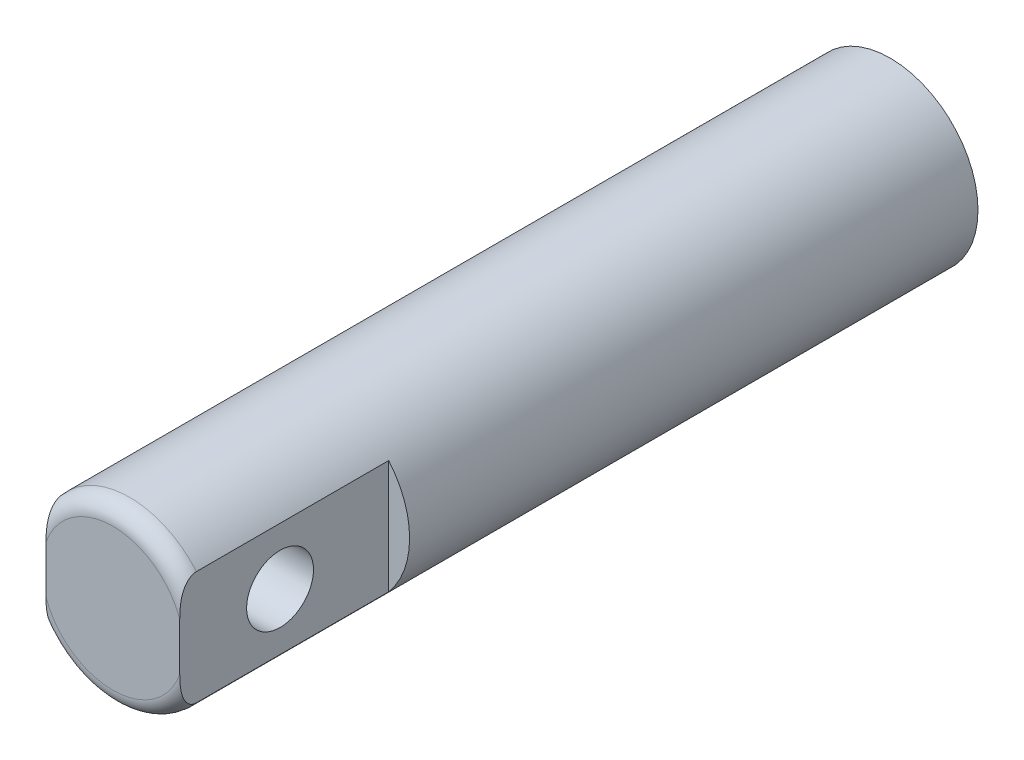
SolidWorks part; units mm, degrees
ref_plane "Спереди" through (0, 0, 0) normal (0, 0, 1) x (1, 0, 0)
ref_plane "Сверху" through (0, 0, 0) normal (0, 1, 0) x (1, 0, 0)
ref_plane "Справа" through (0, 0, 0) normal (1, 0, 0) x (0, 0, -1)
sketch "Эскиз1" plane through (0, 0, 0) normal (0, 0, 1) x (1, 0, 0)
  circle A1 centre (0, 0) radius 10.5
  dimension "D2" = 21
extrude "Вытянуть1" add sketch "Эскиз1" along normal blind 93
sketch "Эскиз2" plane through (0, 0, 0) normal (0, 0, -1) x (-1, 0, 0)
  circle A0 centre (0, 0) radius 5.25
  dimension "D1" = 10.5
extrude "Вытянуть2" cut sketch "Эскиз2" against normal blind 70
fillet "Скругление1" radius 2 1 edges at (10.5, 0, 93)
sketch "Эскиз3" plane through (0, 0, 0) normal (0, 1, 0) x (1, 0, 0)
  line L0 (0, -96.0371) -> (0, -78.1567) construction
  line L1 (-9, -46.6407) -> (-9, -79.7003) construction
  line L2 (9, -46.7694) -> (9, -75.0694) construction
  line L3 (-4.2754, -93) -> (22.1515, -93) construction
  line L5 (-8, -93) -> (-8, -68)
  line L6 (-8, -68) -> (-19, -68)
  line L7 (-19, -68) -> (-19, -93)
  line L8 (-19, -93) -> (-8, -93)
  line L9 (19, -93) -> (8, -93)
  line L10 (8, -93) -> (8, -68)
  line L11 (19, -68) -> (19, -93)
  line L12 (8, -68) -> (19, -68)
  dimension "D1" = 9
  dimension "D2" = 9
  dimension "D3" = 8
  dimension "D4" = 8
  dimension "D5" = 19
  dimension "D6" = 19
  dimension "D9" = 93
  dimension "D10" = 93
extrude "Вытянуть3" cut sketch "Эскиз3" against normal mid plane 30
sketch "Эскиз4" plane through (0, 0, 0) normal (1, 0, 0) x (0, 0, -1)
  line L0 (-93, 7.9341) -> (-93, 25.5987) construction
  line L2 (1.1785, 0) -> (-15.3316, 0) construction
  circle A0 centre (-81, 0) radius 4
  dimension "D1" = 12
  dimension "D2" = 8
  dimension "D3" = 81
extrude "Вытянуть4" cut sketch "Эскиз4" against normal mid plane 30
